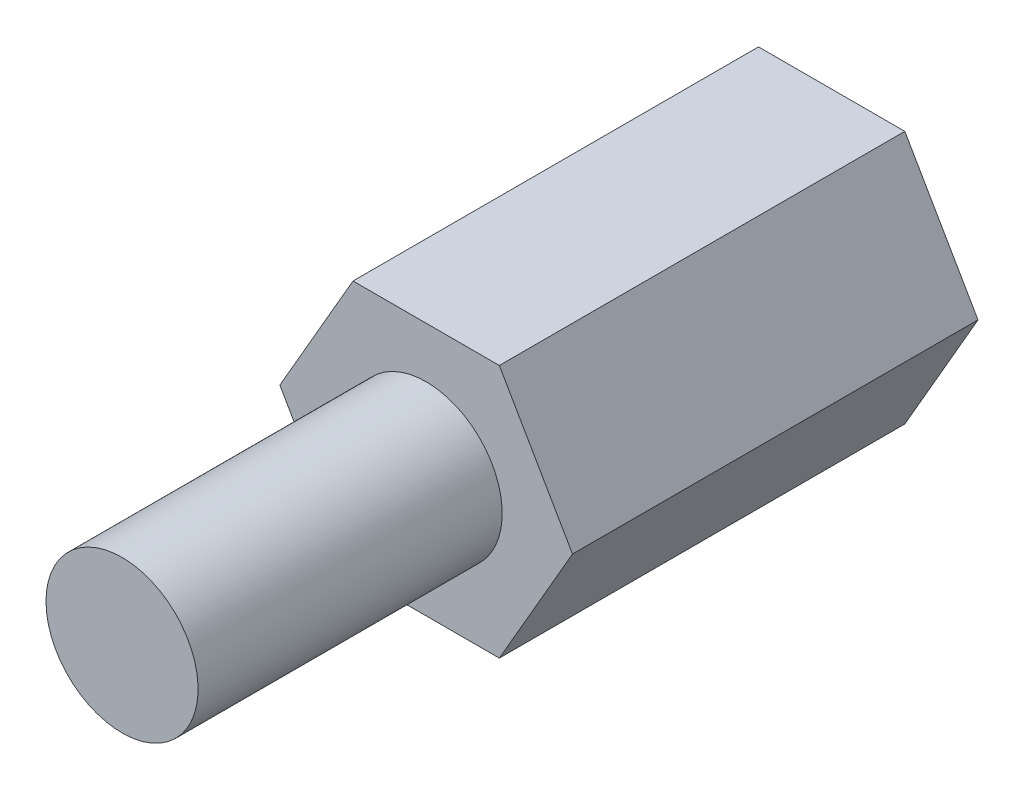
SolidWorks part; units mm, degrees
ref_plane "前视基准面" through (0, 0, 0) normal (0, 0, 1) x (1, 0, 0)
ref_plane "上视基准面" through (0, 0, 0) normal (0, 1, 0) x (1, 0, 0)
ref_plane "右视基准面" through (0, 0, 0) normal (1, 0, 0) x (0, 0, -1)
sketch "草图1" plane through (0, 0, 0) normal (0, 0, 1) x (1, 0, 0)
  line L0 (-28.6627, 0) -> (33.6774, 0) construction
  line L1 (1.4434, -2.5) -> (2.8868, 0)
  line L2 (2.8868, 0) -> (1.4434, 2.5)
  line L3 (1.4434, 2.5) -> (-1.4434, 2.5)
  line L4 (-1.4434, 2.5) -> (-2.8868, 0)
  line L5 (-2.8868, 0) -> (-1.4434, -2.5)
  line L6 (-1.4434, -2.5) -> (1.4434, -2.5)
  circle A0 centre (0, 0) radius 2.5 construction
  dimension "D1" = 5
extrude "拉伸1" add sketch "草图1" along normal blind 8
sketch "草图2" plane through (0, 0, 8) normal (0, 0, 1) x (1, 0, 0)
  circle A0 centre (0, 0) radius 1.5
  dimension "D1" = 3
extrude "拉伸2" add sketch "草图2" along normal blind 6
hole_wizard "M3x0.5 螺纹孔1" positions "3D草图2" profile "草图5" tap size "M3x0.5" standard "ISO"
sketch3d "3D草图2"
  point P0 (0, 0, 0)
  point P2 (0, 0, 0)
  point P3 (0, 0, 0)
  point P4 (0, 0, 0)
cosmetic thread "孔螺蚊线1" parameters "D1"=4, "D2"=3
sketch "草图5" plane through (0, 0, 0) normal (1, 0, 0) x (0, 1, 0)
  line L0 (0, 0) -> (0, 7.2511)
  line L1 (0, 7.2511) -> (1.25, 6.5)
  line L2 (1.25, 6.5) -> (1.25, 0)
  line L5 (1.25, 0) -> (0, 0)
  line L10 (0, 7.2511) -> (-1.25, 6.5) construction
  line L11 (0, -6.35) -> (0, 107.95) construction
  dimension "蹟恇謂郰芛眻噤" = 2.5
  dimension "蹟恇謂郰芛旮僅" = 6.5
  dimension "絳芛褒僅" = 118
sketch "草图6" plane through (0, 0, 0) normal (0, 0, -1) x (-1, 0, 0)
  circle A0 centre (0, 0) radius 1.5
  dimension "D1" = 3
extrude "拉伸3" add sketch "草图6" along normal blind 10
